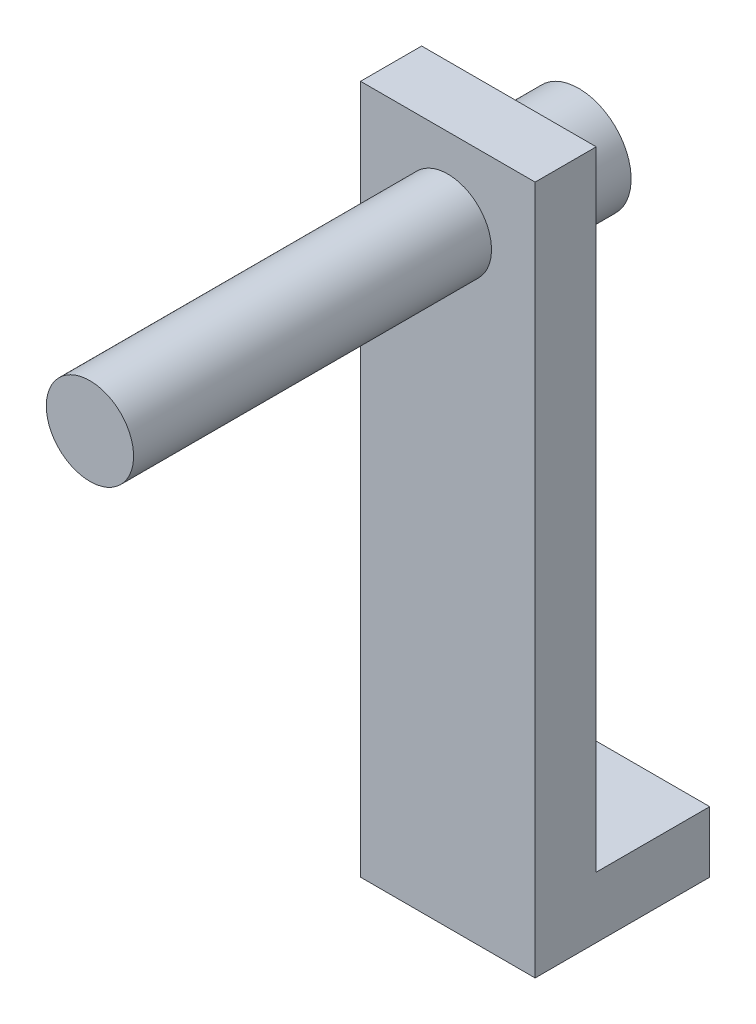
SolidWorks part; units mm, degrees
ref_plane "Спереди" through (0, 0, 0) normal (0, 0, 1) x (1, 0, 0)
ref_plane "Сверху" through (0, 0, 0) normal (0, 1, 0) x (1, 0, 0)
ref_plane "Справа" through (0, 0, 0) normal (1, 0, 0) x (0, 0, -1)
sketch "Эскиз2" plane through (0, 0, 0) normal (0, 1, 0) x (1, 0, 0)
  line L0 (-10, 10) -> (10, -10) construction
  line L5 (-10, 10) -> (10, 10)
  line L6 (-10, 10) -> (-10, -10)
  line L7 (-10, -10) -> (10, -10)
  line L8 (10, 10) -> (10, -10)
  line L9 (-10, -10) -> (10, 10) construction
  point P4 (0, 0)
  dimension "D1" = 20
  dimension "D2" = 20
extrude "Бобышка-Вытянуть2" add sketch "Эскиз2" along normal blind 7
sketch "Эскиз4" plane through (0, 0, 0) normal (0, -1, 0) x (-1, 0, 0)
  line L0 (10, 10) -> (10, -10) construction
  line L1 (-10, -10) -> (10, -10)
  line L2 (-10, -10) -> (-10, -3)
  line L3 (-10, -3) -> (10, -3)
  line L4 (10, -10) -> (10, -3)
  dimension "D1" = 7
extrude "Бобышка-Вытянуть3" add sketch "Эскиз4" against normal blind 78.96
sketch "Эскиз5" plane through (0, 0, 3) normal (0, 0, -1) x (-1, 0, 0)
  line L0 (10, 78.96) -> (-10, 78.96) construction
  circle A0 centre (0, 69.76) radius 5
  dimension "D2" = 10
extrude "Бобышка-Вытянуть4" add sketch "Эскиз5" against normal blind 48
sketch "Эскиз7" plane through (0, 0, 10) normal (0, 0, 1) x (1, 0, 0)
  line L0 (10, 78.96) -> (10, 0) construction
  line L1 (-10, 78.96) -> (10, 78.96)
  line L2 (-10, 78.96) -> (-10, 59.0869)
  line L3 (-10, 59.0869) -> (10, 59.0869)
  line L4 (10, 78.96) -> (10, 59.0869)
ref_plane "SettingPlane" through (0, 0, 10) normal (0, 0, -1) x (-1, 0, 0)
sketch "Эскиз10" plane through (0, 0, 3) normal (0, 0, -1) x (-1, 0, 0)
  line L0 (0, 78.96) -> (0, 69.76) construction
  line L1 (10, 78.96) -> (-10, 78.96) construction
  circle A0 centre (0, 69.76) radius 5.9974
extrude "Бобышка-Вытянуть5" add sketch "Эскиз10" along normal blind 8
